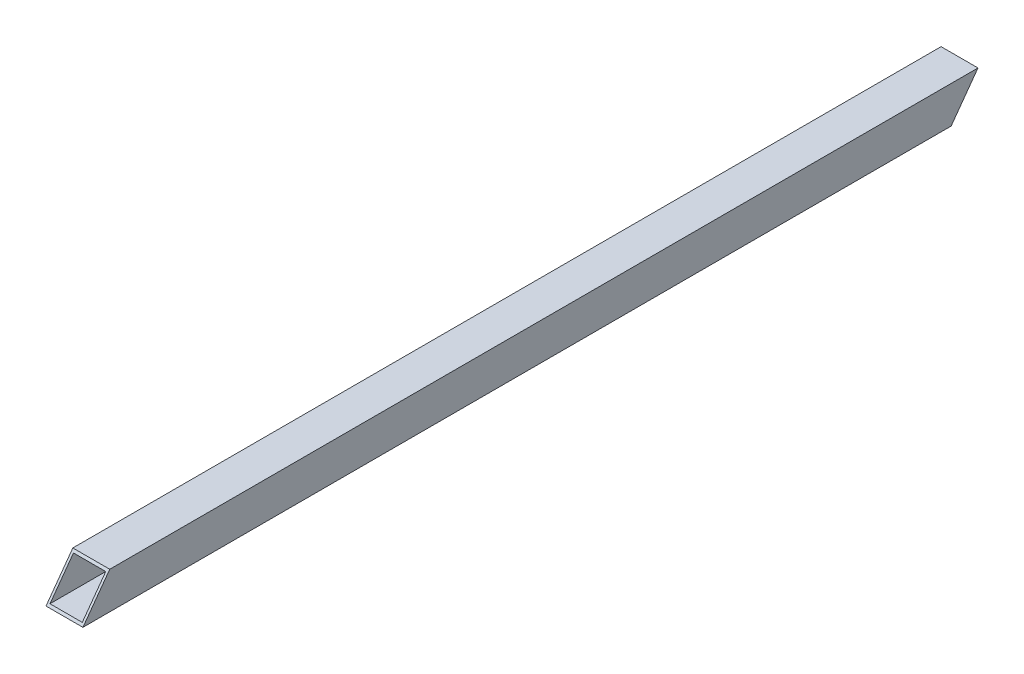
SolidWorks part; units mm, degrees
material "AISI 1020"
ref_plane "Front Plane" through (0, 0, 0) normal (0, 0, 1) x (1, 0, 0)
ref_plane "Top Plane" through (0, 0, 0) normal (0, 1, 0) x (1, 0, 0)
ref_plane "Right Plane" through (0, 0, 0) normal (1, 0, 0) x (0, 0, -1)
sketch "Sketch1" plane through (0, 0, 0) normal (0, 0, 1) x (1, 0, 0)
  line L0 (22.225, 22.225) -> (22.225, 25.4) construction
  line L1 (-25.4, -25.4) -> (25.4, -25.4)
  line L2 (-25.4, -25.4) -> (-25.4, 25.4)
  line L3 (-25.4, 25.4) -> (25.4, 25.4)
  line L4 (25.4, -25.4) -> (25.4, 25.4)
  line L5 (-25.4, -25.4) -> (25.4, 25.4) construction
  line L6 (-25.4, 25.4) -> (25.4, -25.4) construction
  line L7 (-22.225, -22.225) -> (22.225, -22.225)
  line L8 (-22.225, -22.225) -> (-22.225, 22.225)
  line L9 (-22.225, 22.225) -> (22.225, 22.225)
  line L10 (22.225, -22.225) -> (22.225, 22.225)
  line L11 (-22.225, -22.225) -> (22.225, 22.225) construction
  line L12 (-22.225, 22.225) -> (22.225, -22.225) construction
  line L13 (22.225, -22.225) -> (25.4, -22.225) construction
  point P0 (0, 0)
  point P6 (0, 0)
  dimension "D2" = 50.8
  dimension "D3" = 3.175
extrude "Boss-Extrude1" add sketch "Sketch1" along normal blind 1231.9
sketch "Sketch2" plane through (-25.4, 0, 0) normal (-1, 0, 0) x (0, 0, 1)
  line L0 (0, 25.4) -> (36.9084, -25.4)
  line L1 (1231.9, -25.4) -> (0, -25.4) construction
  line L2 (36.9084, -25.4) -> (0, -25.4)
  line L3 (0, -25.4) -> (0, 25.4)
  dimension "D1" = 54
extrude "Cut-Extrude1" cut sketch "Sketch2" against normal through all
sketch "Sketch3" plane through (-25.4, 0, 0) normal (-1, 0, 0) x (0, 0, 1)
  line L0 (1231.9, -25.4) -> (1194.9916, 25.4)
  line L1 (1231.9, 25.4) -> (0, 25.4) construction
  line L2 (1194.9916, 25.4) -> (1231.9, 25.4)
  line L3 (1231.9, 25.4) -> (1231.9, -25.4)
  dimension "D1" = 54
extrude "Cut-Extrude2" cut sketch "Sketch3" against normal through all contours L0 L2 L3
